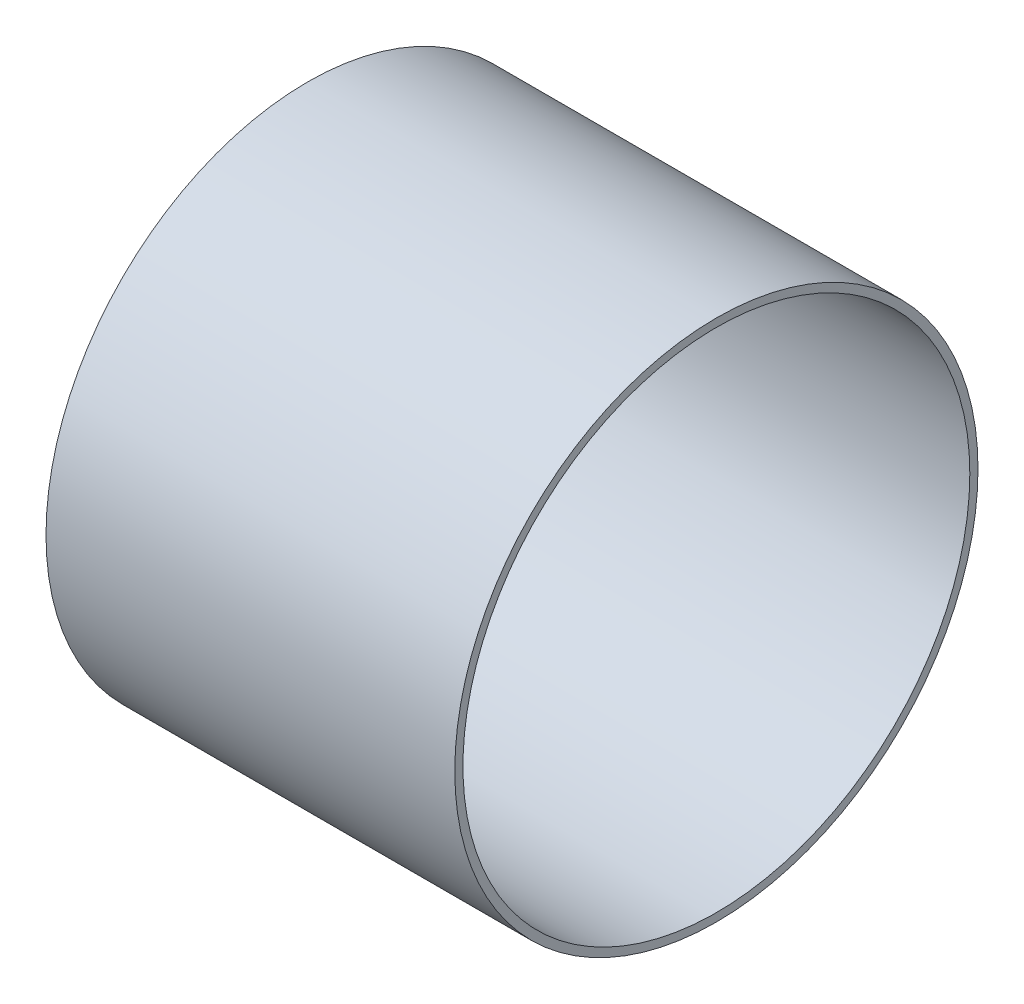
SolidWorks part; units mm, degrees
material "ABS"
ref_plane "Front Plane" through (0, 0, 0) normal (0, 0, 1) x (1, 0, 0)
ref_plane "Top Plane" through (0, 0, 0) normal (0, 1, 0) x (1, 0, 0)
ref_plane "Right Plane" through (0, 0, 0) normal (1, 0, 0) x (0, 0, -1)
sketch "Sketch1" plane through (0, 0, 0) normal (1, 0, 0) x (0, 0, -1)
  circle A0 centre (0, 0) radius 31.496
  circle A1 centre (0, 0) radius 32.512
  dimension "D1" = 65.024
  dimension "D2" = 62.992
extrude "Boss-Extrude1" add sketch "Sketch1" along normal blind 50.8
